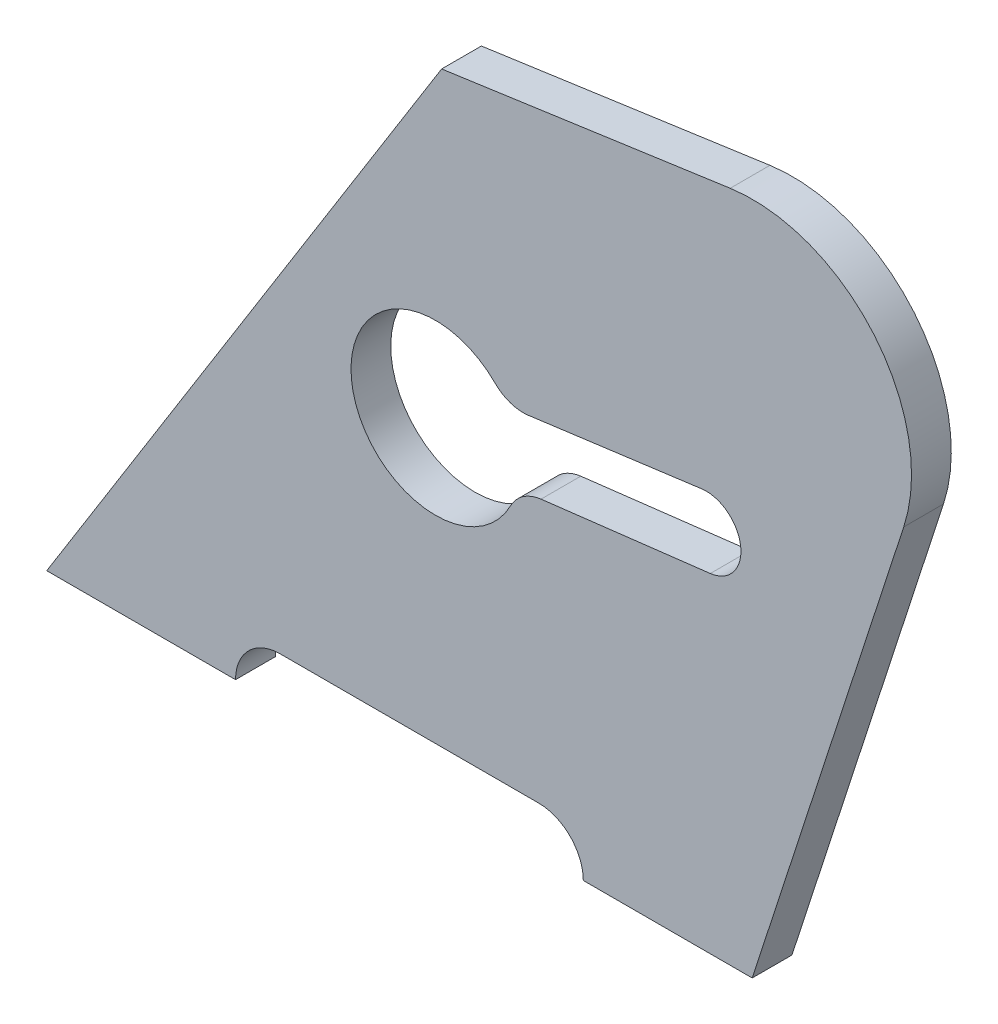
SolidWorks part; units mm, degrees
ref_plane "Front Plane" through (0, 0, 0) normal (0, 0, 1) x (1, 0, 0)
ref_plane "Top Plane" through (0, 0, 0) normal (0, 1, 0) x (1, 0, 0)
ref_plane "Right Plane" through (0, 0, 0) normal (1, 0, 0) x (0, 0, -1)
sketch "Sketch2" plane through (0, 0, 0) normal (0, 0, 1) x (1, 0, 0)
  line L0 (0, 0) -> (79.4879, 127.2072)
  line L1 (0, 0) -> (38, 0)
  line L2 (47, 9) -> (99, 9)
  line L3 (108, 0) -> (142, 0)
  line L4 (142, 0) -> (167.3394, 77.9866)
  line L5 (137.573, 135.4513) -> (79.4879, 127.2072)
  line L6 (78.2447, 65.7777) -> (132.7354, 73.2448)
  line L7 (131.8149, 80.184) -> (96.9415, 75.5577)
  line L8 (133.5656, 66.2942) -> (99.4957, 62.2248)
  line L9 (78.2447, 65.7777) -> (37.6243, 60.2114)
  line L10 (132.7354, 73.2448) -> (167.3394, 77.9866)
  line L11 (137.573, 135.4513) -> (188.3525, 142.6585) construction
  line L12 (172.5035, 93.8803) -> (188.3525, 142.6585) construction
  line L14 (167.3394, 77.9866) -> (172.5035, 93.8803)
  arc A0 (38, 0) -> (47, 9) centre (47, 0) cw
  arc A1 (99, 9) -> (108, 0) centre (99, 0) cw
  arc A3 (90.2431, 77.8209) -> (93.3405, 57.9601) centre (78.2447, 65.7777) ccw
  arc A4 (133.5656, 66.2942) -> (131.8149, 80.184) centre (132.7354, 73.2448) ccw
  arc A5 (99.4957, 62.2248) -> (93.3405, 57.9601) centre (100.4445, 54.2813) ccw
  arc A6 (96.9415, 75.5577) -> (90.2431, 77.8209) centre (95.8894, 83.4883) cw
  arc A7 (137.573, 135.4513) -> (172.5035, 93.8803) centre (142.0697, 103.7688) cw
  point P9 (0, 0)
  point P11 (0, 0)
  point P26 (188.3525, 142.6585)
  dimension "D2" = 9
  dimension "D4" = 9
  dimension "D5" = 9
  dimension "D10" = 150
  dimension "D11" = 7
  dimension "D13" = 17
  dimension "D14" = 8
  dimension "D15" = 41
  dimension "D18" = 32
  dimension "D1" = 58
  dimension "D3" = 108
  dimension "D6" = 52
  dimension "D7" = 47
  dimension "D8" = 142
  dimension "D9" = 150
  dimension "D12" = 55
  dimension "D16" = 71
  dimension "D17" = 82
extrude "Boss-Extrude1" add sketch "Sketch2" along normal blind 8 contours A7 L5 L0 L9 A3 A6 L7 A4 L10 L14 | L8 A5 A3 L9 L0 L1 A0 L2 A1 L3 L4 L10 A4
